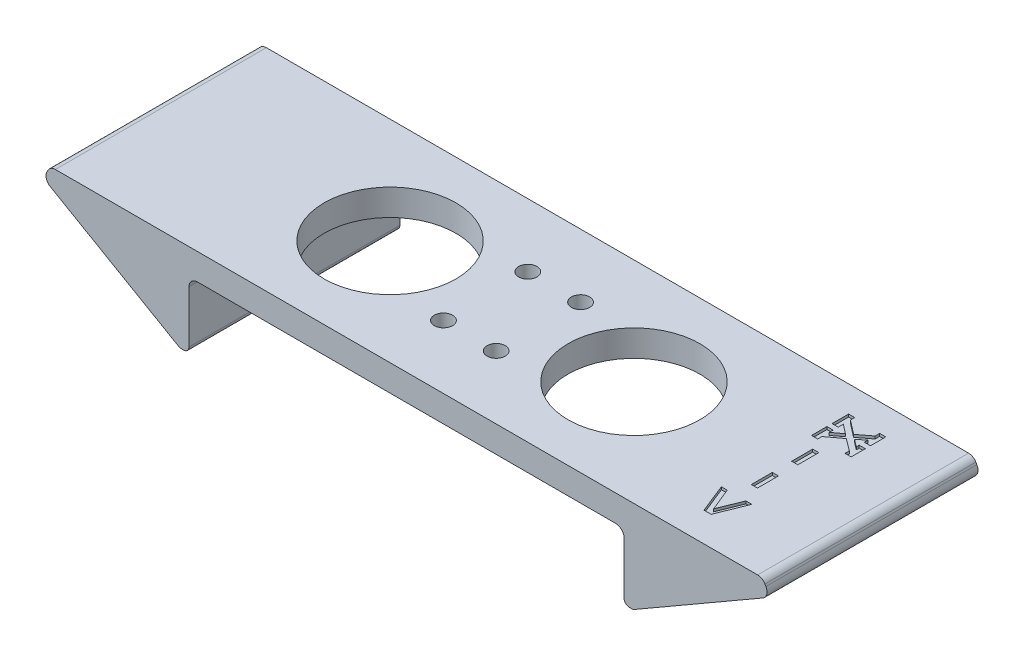
SolidWorks part; units mm, degrees
ref_plane "Front Plane" through (0, 0, 0) normal (0, 0, 1) x (1, 0, 0)
ref_plane "Top Plane" through (0, 0, 0) normal (0, 1, 0) x (1, 0, 0)
ref_plane "Right Plane" through (0, 0, 0) normal (1, 0, 0) x (0, 0, -1)
sketch "Sketch1" plane through (0, 0, 0) normal (0, 0, 1) x (1, 0, 0)
  line L0 (85.725, 0) -> (-85.725, 0)
  line L1 (-85.725, 0) -> (-87.5581, -3.175)
  line L2 (-87.5581, -3.175) -> (-54.5625, -22.225)
  line L3 (-54.5625, -22.225) -> (-52.3875, -22.225)
  line L4 (-52.3875, -22.225) -> (-52.3875, -6.35)
  line L5 (-52.3875, -6.35) -> (52.3875, -6.35)
  line L6 (0, 0) -> (0, -6.35) construction
  line L7 (52.3875, -22.225) -> (52.3875, -6.35)
  line L8 (54.5625, -22.225) -> (52.3875, -22.225)
  line L9 (87.5581, -3.175) -> (54.5625, -22.225)
  line L10 (85.725, 0) -> (87.5581, -3.175)
  point P14 (52.3875, -14.2875)
  dimension "D1" = 120
  dimension "D2" = 6.35
  dimension "D3" = 38.1
  dimension "D4" = 171.45
  dimension "D5" = 104.775
  dimension "D6" = 3.175
extrude "Boss-Extrude1" add sketch "Sketch1" along normal blind 50.8
fillet "Fillet1" radius 2.032 6 edges at (-87.5581, -3.175, 25.4) (87.5581, -3.175, 25.4) (-52.3875, -6.35, 25.4) (52.3875, -6.35, 25.4) (-85.725, 0, 25.4) (85.725, 0, 25.4)
fillet "Fillet2" radius 1.27 4 edges at (-54.5625, -22.225, 25.4) (-52.3875, -22.225, 25.4) (54.5625, -22.225, 25.4) (52.3875, -22.225, 25.4)
sketch "Sketch2" plane through (0, 0, 0) normal (0, 1, 0) x (1, 0, 0)
  line L0 (0, -50.8) -> (0, 0) construction
  line L1 (84.5518, -50.8) -> (-84.5518, -50.8) construction
  line L2 (-52.3875, 0) -> (-52.3875, -50.8) construction
  line L3 (-6.35, -15.24) -> (6.35, -15.24) construction
  line L4 (-6.35, -15.24) -> (-6.35, -35.56) construction
  line L5 (-6.35, -35.56) -> (6.35, -35.56) construction
  line L6 (6.35, -15.24) -> (6.35, -35.56) construction
  line L7 (0, -35.56) -> (0, -15.24) construction
  line L8 (-6.35, -25.4) -> (6.35, -25.4) construction
  line L9 (52.3875, -50.8) -> (52.3875, 0) construction
  line L10 (-52.3875, 0) -> (-52.3875, -50.8) construction
  line L11 (52.3875, -50.8) -> (52.3875, 0) construction
  line L12 (6.35, -25.4) -> (52.3875, -25.4) construction
  circle A0 centre (6.35, -35.56) radius 2.1971
  circle A1 centre (-6.35, -35.56) radius 2.1971
  circle A2 centre (-6.35, -15.24) radius 2.1971
  circle A3 centre (6.35, -15.24) radius 2.1971
  circle A4 centre (29.3687, -25.4) radius 15.875
  circle A5 centre (-29.3687, -25.4) radius 15.875
  point P5 (0, -25.4)
  dimension "D1" = 4.3942
  dimension "D4" = 31.75
  dimension "D2" = 12.7
  dimension "D3" = 20.32
extrude "Cut-Extrude1" cut sketch "Sketch2" against normal through all
sketch "Sketch3" plane through (0, 0, 0) normal (0, 1, 0) x (1, 0, 0)
  line L0 (61.9434, 0) -> (61.9434, -50.8) construction
  line L1 (84.5518, 0) -> (-84.5518, 0) construction
  line L2 (84.5518, -50.8) -> (-84.5518, -50.8) construction
  text T0 "<b>X--></b>" font "Courier Std" height in points 36
extrude "Cut-Extrude2" cut sketch "Sketch3" against normal blind 0.635
